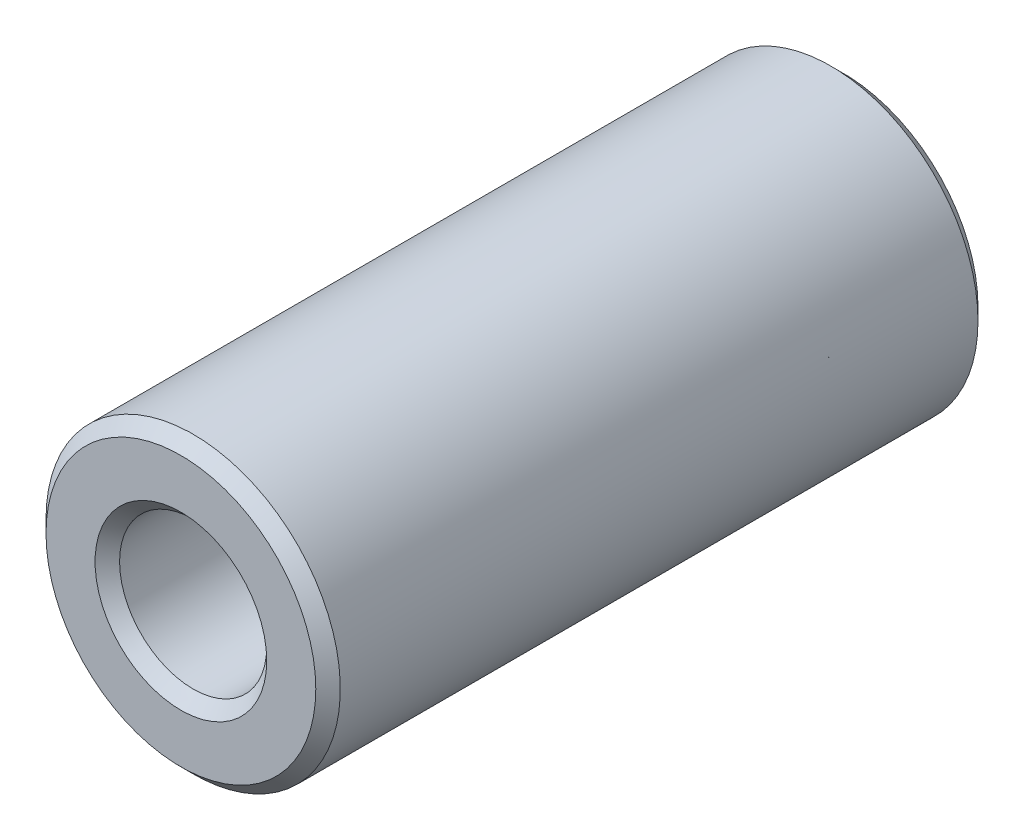
SolidWorks part; units mm, degrees
ref_plane "Plan1" through (0, 0, 0) normal (0, 0, 1) x (1, 0, 0)
ref_plane "Plan2" through (0, 0, 0) normal (0, 1, 0) x (1, 0, 0)
ref_plane "Plan3" through (0, 0, 0) normal (1, 0, 0) x (0, 0, -1)
sketch "Esquisse1" plane through (0, 0, 0) normal (0, 0, 1) x (1, 0, 0)
  circle A0 centre (0, 0) radius 6
  circle A1 centre (0, 0) radius 3
  dimension "D1" = 12
  dimension "D2" = 6
extrude "Base-Extrusion" add sketch "Esquisse1" along normal blind 27
chamfer "Chanfrein1" distance 0.5 angle 45
